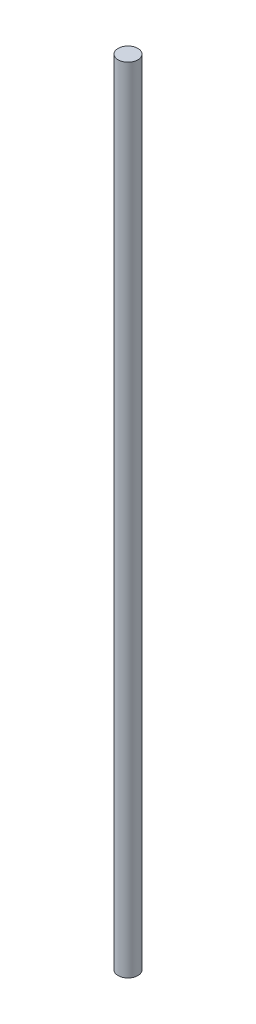
SolidWorks part; units mm, degrees
ref_plane "Front Plane" through (0, 0, 0) normal (0, 0, 1) x (1, 0, 0)
ref_plane "Top Plane" through (0, 0, 0) normal (0, 1, 0) x (1, 0, 0)
ref_plane "Right Plane" through (0, 0, 0) normal (1, 0, 0) x (0, 0, -1)
sketch "Sketch1" plane through (0, 0, 0) normal (0, 1, 0) x (1, 0, 0)
  circle A0 centre (0, 0) radius 2.5
  dimension "D1" = 5
extrude "Boss-Extrude1" add sketch "Sketch1" along normal mid plane 200
